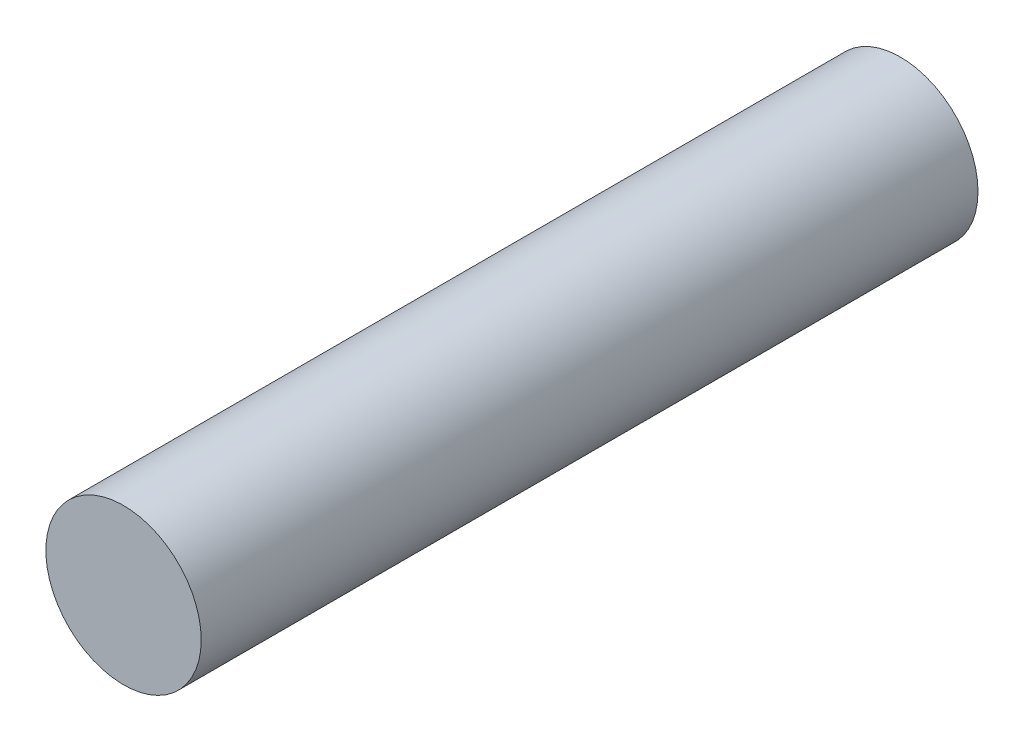
SolidWorks part; units mm, degrees
ref_plane "정면" through (0, 0, 0) normal (0, 0, 1) x (1, 0, 0)
ref_plane "윗면" through (0, 0, 0) normal (0, 1, 0) x (1, 0, 0)
ref_plane "우측면" through (0, 0, 0) normal (1, 0, 0) x (0, 0, -1)
sketch "스케치1" plane through (0, 0, 0) normal (0, 0, 1) x (1, 0, 0)
  circle A0 centre (0, 0) radius 20
  dimension "D1" = 40
extrude "보스-돌출1" add sketch "스케치1" along normal blind 200
